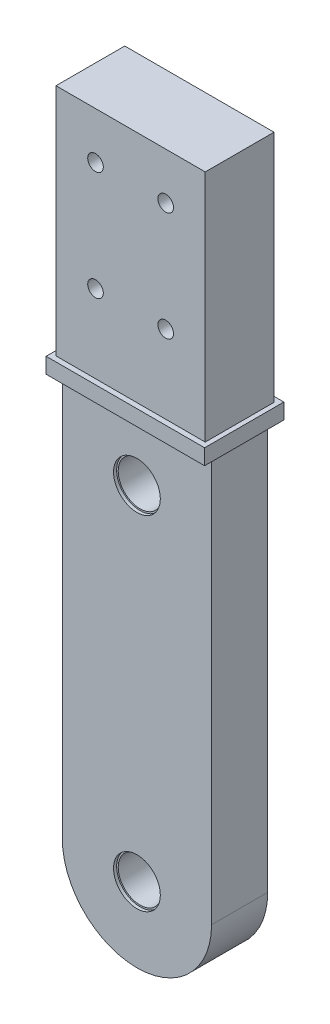
SolidWorks part; units mm, degrees
ref_plane "Front Plane" through (0, 0, 0) normal (0, 0, 1) x (1, 0, 0)
ref_plane "Top Plane" through (0, 0, 0) normal (0, 1, 0) x (1, 0, 0)
ref_plane "Right Plane" through (0, 0, 0) normal (1, 0, 0) x (0, 0, -1)
sketch "Sketch1" plane through (0, 0, 0) normal (0, 0, 1) x (1, 0, 0)
  line L0 (-23.925, 0) -> (-23.925, 100)
  line L1 (-23.925, 100) -> (23.925, 100)
  line L2 (23.925, 100) -> (23.925, 0)
  line L3 (-23.925, 0) -> (-23.925, -110)
  line L4 (-11.25, 85) -> (11.25, 85) construction
  line L5 (-11.25, 85) -> (-11.25, 50) construction
  line L6 (-11.25, 50) -> (11.25, 50) construction
  line L7 (11.25, 85) -> (11.25, 50) construction
  line L8 (0, 0) -> (0, -110) construction
  line L10 (23.925, 0) -> (23.925, -110)
  circle A0 centre (0, 0) radius 7
  circle A2 centre (-11.25, 85) radius 2.5
  circle A3 centre (11.25, 85) radius 2.5
  circle A4 centre (11.25, 50) radius 2.5
  circle A5 centre (-11.25, 50) radius 2.5
  circle A6 centre (0, -110) radius 7
  arc A7 (23.925, -110) -> (0, -133.925) centre (0, -110) cw
  arc A8 (-23.925, -110) -> (0, -133.925) centre (0, -110) ccw
  point P13 (0, 50)
  point P25 (0, 100)
  dimension "D1" = 14
  dimension "D4" = 5
  dimension "D9" = 14
  dimension "D11" = 23.925
  dimension "D2" = 47.85
  dimension "D3" = 100
  dimension "D5" = 35
  dimension "D6" = 15
  dimension "D7" = 22.5
  dimension "D8" = 110
extrude "Boss-Extrude1" add sketch "Sketch1" along normal mid plane 18 from surface at 0 starting at plane "Front Plane"
sketch "Sketch3" plane through (0, 0, 0) normal (0, 0, 1) x (1, 0, 0)
  line L0 (23.925, 100) -> (23.925, -110) construction
  line L1 (-23.925, 100) -> (23.925, 100)
  line L2 (-23.925, 100) -> (-23.925, 35)
  line L3 (-23.925, 35) -> (23.925, 35)
  line L4 (23.925, 100) -> (23.925, 35)
  line L5 (-11.25, 85) -> (-11.25, 100) construction
  line L6 (-11.25, 50) -> (-11.25, 35) construction
  circle A0 centre (-11.25, 50) radius 2.5
  circle A1 centre (11.25, 50) radius 2.5
  circle A2 centre (11.25, 85) radius 2.5
  circle A3 centre (-11.25, 85) radius 2.5
  circle A4 centre (-11.25, 85) radius 2.5 construction
extrude "Boss-Extrude2" add sketch "Sketch3" along normal mid plane 22.05
sketch "Sketch4" plane through (0, 0, 9) normal (0, 0, 1) x (1, 0, 0)
  circle A0 centre (0, -110) radius 7.5
  dimension "D1" = 15
extrude "Cut-Extrude1" cut sketch "Sketch4" against normal blind 1
sketch "Sketch5" plane through (0, 0, -9) normal (0, 0, -1) x (-1, 0, 0)
  circle A0 centre (0, -110) radius 7.5
  dimension "D1" = 15
extrude "Cut-Extrude2" cut sketch "Sketch5" against normal blind 1
sketch "Sketch6" plane through (0, 0, 9) normal (0, 0, 1) x (1, 0, 0)
  circle A0 centre (0, 0) radius 7.5
  dimension "D1" = 15
extrude "Cut-Extrude3" cut sketch "Sketch6" against normal blind 1
sketch "Sketch7" plane through (0, 0, -9) normal (0, 0, -1) x (-1, 0, 0)
  circle A0 centre (0, 0) radius 7.5
  dimension "D1" = 15
extrude "Cut-Extrude4" cut sketch "Sketch7" against normal blind 1
sketch "Sketch8" plane through (0, 35, 0) normal (0, -1, 0) x (1, 0, 0)
  line L1 (-25.4, -12.7) -> (25.4, -12.7)
  line L2 (-25.4, -12.7) -> (-25.4, 12.7)
  line L3 (-25.4, 12.7) -> (25.4, 12.7)
  line L4 (25.4, -12.7) -> (25.4, 12.7)
  line L5 (-25.4, -12.7) -> (25.4, 12.7) construction
  line L6 (-25.4, 12.7) -> (25.4, -12.7) construction
  point P0 (0, 0)
  dimension "D1" = 50.8
  dimension "D2" = 25.4
extrude "Boss-Extrude3" add sketch "Sketch8" along normal blind 5 from offset 10
sketch "Sketch9" plane through (0, 35, 0) normal (0, -1, 0) x (1, 0, 0)
  line L1 (-23.925, -11.025) -> (23.925, -11.025)
  line L2 (-23.925, -11.025) -> (-23.925, 11.025)
  line L3 (-23.925, 11.025) -> (23.925, 11.025)
  line L4 (23.925, -11.025) -> (23.925, 11.025)
  line L5 (-23.925, -11.025) -> (23.925, 11.025) construction
  line L6 (-23.925, 11.025) -> (23.925, -11.025) construction
  point P0 (0, 0)
extrude "Boss-Extrude4" add sketch "Sketch9" along normal up to surface (10 mm away) up to face at (0, 25, 0)
equation "\"tube_length\"= 1.5ft"
